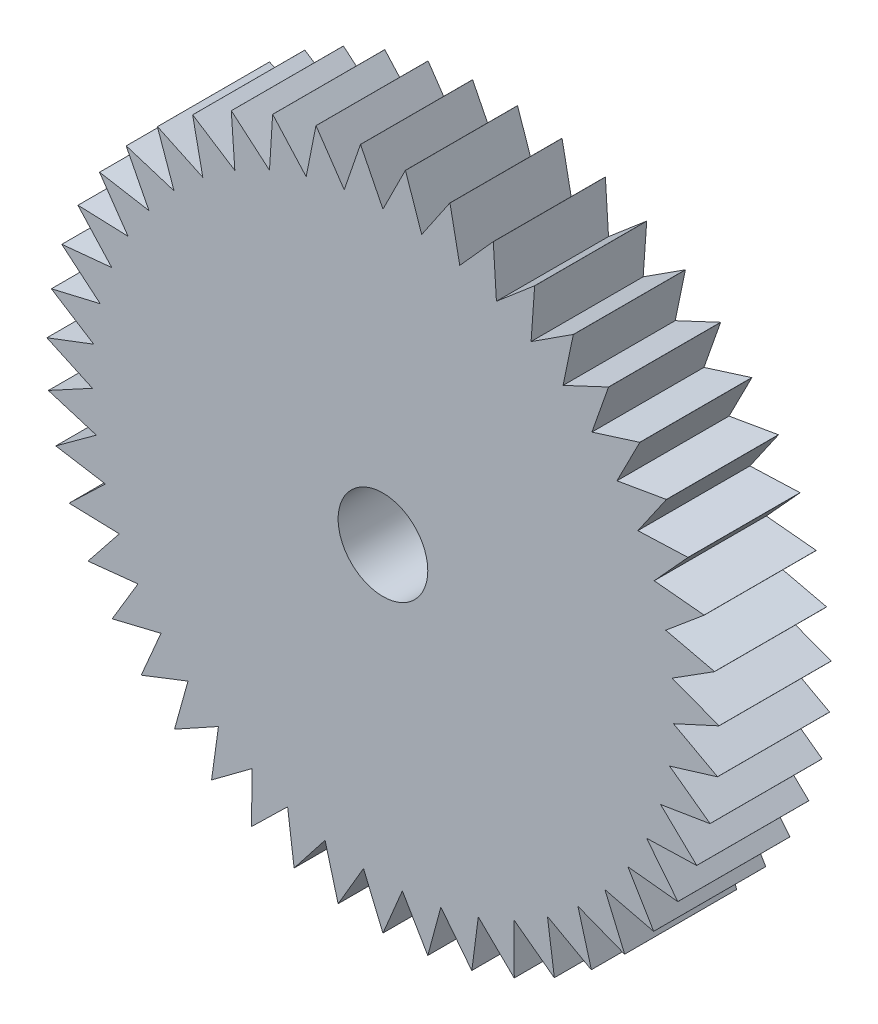
SolidWorks part; units mm, degrees
ref_plane "Alzado" through (0, 0, 0) normal (0, 0, 1) x (1, 0, 0)
ref_plane "Planta" through (0, 0, 0) normal (0, 1, 0) x (1, 0, 0)
ref_plane "Vista lateral" through (0, 0, 0) normal (1, 0, 0) x (0, 0, -1)
sketch "Croquis2" plane through (0, 0, 0) normal (0, 0, 1) x (1, 0, 0)
  circle A0 centre (0, 0) radius 2
  circle A1 centre (0, 0) radius 15
  dimension "D1" = 4
  dimension "D2" = 30
extrude "Saliente-Extruir1" add sketch "Croquis2" along normal blind 5
sketch "Croquis3" plane through (0, 0, 5) normal (0, 0, 1) x (1, 0, 0)
  line L0 (-1, 14.9666) -> (0, 12.9666)
  line L1 (0, 12.9666) -> (1, 14.9666)
  line L2 (-1, 14.9666) -> (1, 14.9666) construction
  line L3 (1.0038, 14.9664) -> (1.7283, 12.8509)
  line L4 (1.7283, 12.8509) -> (2.9859, 14.6998)
  line L5 (2.9896, 14.699) -> (3.4257, 12.5059)
  line L6 (3.4257, 12.5059) -> (4.9186, 14.1707)
  line L7 (4.9222, 14.1694) -> (5.062, 11.9377)
  line L8 (5.062, 11.9377) -> (6.7635, 13.3886)
  line L9 (6.7668, 13.3869) -> (6.608, 11.1565)
  line L10 (6.608, 11.1565) -> (8.4876, 12.3677)
  line L11 (8.4908, 12.3656) -> (8.0361, 10.1762)
  line L12 (8.0361, 10.1762) -> (10.0604, 11.1261)
  line L13 (10.0632, 11.1235) -> (9.3207, 9.0143)
  line L14 (9.3207, 9.0143) -> (11.4536, 9.6859)
  line L15 (11.456, 9.683) -> (10.439, 7.6915)
  line L16 (10.439, 7.6915) -> (12.6424, 8.0728)
  line L17 (12.6444, 8.0696) -> (11.3711, 6.2315)
  line L18 (11.3711, 6.2315) -> (13.6056, 6.3157)
  line L19 (13.6072, 6.3123) -> (12.1002, 4.6603)
  line L20 (12.1002, 4.6603) -> (14.326, 4.4459)
  line L21 (14.3271, 4.4423) -> (12.6134, 3.0059)
  line L22 (12.6134, 3.0059) -> (14.7907, 2.4968)
  line L23 (14.7914, 2.4931) -> (12.9015, 1.2979)
  line L24 (12.9015, 1.2979) -> (14.9916, 0.5031)
  line L25 (14.9917, 0.4993) -> (12.9594, -0.4333)
  line L26 (12.9594, -0.4333) -> (14.9249, -1.4996)
  line L27 (14.9245, -1.5033) -> (12.786, -2.1567)
  line L28 (12.786, -2.1567) -> (14.5918, -3.4755)
  line L29 (14.5909, -3.4791) -> (12.3845, -3.8417)
  line L30 (12.3845, -3.8417) -> (13.9984, -5.3893)
  line L31 (13.997, -5.3929) -> (11.7619, -5.4581)
  line L32 (11.7619, -5.4581) -> (13.1552, -7.2071)
  line L33 (13.1533, -7.2104) -> (10.9295, -6.9771)
  line L34 (10.9295, -6.9771) -> (12.0772, -8.8962)
  line L35 (12.0749, -8.8992) -> (9.902, -8.3716)
  line L36 (9.902, -8.3716) -> (10.7837, -10.4265)
  line L37 (10.781, -10.4292) -> (8.6978, -9.6167)
  line L38 (8.6978, -9.6167) -> (9.2977, -11.7708)
  line L39 (9.2948, -11.7732) -> (7.3384, -10.6902)
  line L40 (7.3384, -10.6902) -> (7.6459, -12.9051)
  line L41 (7.6426, -12.907) -> (5.8481, -11.573)
  line L42 (5.8481, -11.573) -> (5.8576, -13.809)
  line L43 (5.8541, -13.8105) -> (4.2534, -12.2492)
  line L44 (4.2534, -12.2492) -> (3.9648, -14.4665)
  line L45 (3.9611, -14.4675) -> (2.5828, -12.7068)
  line L46 (2.5828, -12.7068) -> (2.0012, -14.8659)
  line L47 (1.9974, -14.8664) -> (0.8661, -12.9377)
  line L48 (0.8661, -12.9377) -> (0.0019, -15)
  line L49 (-0.0019, -15) -> (-0.8661, -12.9377)
  line L50 (-0.8661, -12.9377) -> (-1.9974, -14.8664)
  line L51 (-2.0012, -14.8659) -> (-2.5828, -12.7068)
  line L52 (-2.5828, -12.7068) -> (-3.9611, -14.4675)
  line L53 (-3.9648, -14.4665) -> (-4.2534, -12.2492)
  line L54 (-4.2534, -12.2492) -> (-5.8541, -13.8105)
  line L55 (-5.8576, -13.809) -> (-5.8481, -11.573)
  line L56 (-5.8481, -11.573) -> (-7.6426, -12.907)
  line L57 (-7.6459, -12.9051) -> (-7.3384, -10.6902)
  line L58 (-7.3384, -10.6902) -> (-9.2948, -11.7732)
  line L59 (-9.2977, -11.7708) -> (-8.6978, -9.6167)
  line L60 (-8.6978, -9.6167) -> (-10.781, -10.4292)
  line L61 (-10.7837, -10.4265) -> (-9.902, -8.3716)
  line L62 (-9.902, -8.3716) -> (-12.0749, -8.8992)
  line L63 (-12.0772, -8.8962) -> (-10.9295, -6.9771)
  line L64 (-10.9295, -6.9771) -> (-13.1533, -7.2104)
  line L65 (-13.1552, -7.2071) -> (-11.7619, -5.4581)
  line L66 (-11.7619, -5.4581) -> (-13.997, -5.3929)
  line L67 (-13.9984, -5.3893) -> (-12.3845, -3.8417)
  line L68 (-12.3845, -3.8417) -> (-14.5909, -3.4791)
  line L69 (-14.5918, -3.4755) -> (-12.786, -2.1567)
  line L70 (-12.786, -2.1567) -> (-14.9245, -1.5033)
  line L71 (-14.9249, -1.4996) -> (-12.9594, -0.4333)
  line L72 (-12.9594, -0.4333) -> (-14.9917, 0.4993)
  line L73 (-14.9916, 0.5031) -> (-12.9015, 1.2979)
  line L74 (-12.9015, 1.2979) -> (-14.7914, 2.4931)
  line L75 (-14.7907, 2.4968) -> (-12.6134, 3.0059)
  line L76 (-12.6134, 3.0059) -> (-14.3271, 4.4423)
  line L77 (-14.326, 4.4459) -> (-12.1002, 4.6603)
  line L78 (-12.1002, 4.6603) -> (-13.6072, 6.3123)
  line L79 (-13.6056, 6.3157) -> (-11.3711, 6.2315)
  line L80 (-11.3711, 6.2315) -> (-12.6444, 8.0696)
  line L81 (-12.6424, 8.0728) -> (-10.439, 7.6915)
  line L82 (-10.439, 7.6915) -> (-11.456, 9.683)
  line L83 (-11.4536, 9.6859) -> (-9.3207, 9.0143)
  line L84 (-9.3207, 9.0143) -> (-10.0632, 11.1235)
  line L85 (-10.0604, 11.1261) -> (-8.0361, 10.1762)
  line L86 (-8.0361, 10.1762) -> (-8.4908, 12.3656)
  line L87 (-8.4876, 12.3677) -> (-6.608, 11.1565)
  line L88 (-6.608, 11.1565) -> (-6.7668, 13.3869)
  line L89 (-6.7635, 13.3886) -> (-5.062, 11.9377)
  line L90 (-5.062, 11.9377) -> (-4.9222, 14.1694)
  line L91 (-4.9186, 14.1707) -> (-3.4257, 12.5059)
  line L92 (-3.4257, 12.5059) -> (-2.9896, 14.699)
  line L93 (-2.9859, 14.6998) -> (-1.7283, 12.8509)
  line L94 (-1.7283, 12.8509) -> (-1.0038, 14.9664)
  arc A0 (1, 14.9666) -> (-1, 14.9666) centre (0, 0) ccw
  arc A1 (2.9859, 14.6998) -> (1.0038, 14.9664) centre (0, 0) ccw
  arc A2 (4.9186, 14.1707) -> (2.9896, 14.699) centre (0, 0) ccw
  arc A3 (6.7635, 13.3886) -> (4.9222, 14.1694) centre (0, 0) ccw
  arc A4 (8.4876, 12.3677) -> (6.7668, 13.3869) centre (0, 0) ccw
  arc A5 (10.0604, 11.1261) -> (8.4908, 12.3656) centre (0, 0) ccw
  arc A6 (11.4536, 9.6859) -> (10.0632, 11.1235) centre (0, 0) ccw
  arc A7 (12.6424, 8.0728) -> (11.456, 9.683) centre (0, 0) ccw
  arc A8 (13.6056, 6.3157) -> (12.6444, 8.0696) centre (0, 0) ccw
  arc A9 (14.326, 4.4459) -> (13.6072, 6.3123) centre (0, 0) ccw
  arc A10 (14.7907, 2.4968) -> (14.3271, 4.4423) centre (0, 0) ccw
  arc A11 (14.9916, 0.5031) -> (14.7914, 2.4931) centre (0, 0) ccw
  arc A12 (14.9249, -1.4996) -> (14.9917, 0.4993) centre (0, 0) ccw
  arc A13 (14.5918, -3.4755) -> (14.9245, -1.5033) centre (0, 0) ccw
  arc A14 (13.9984, -5.3893) -> (14.5909, -3.4791) centre (0, 0) ccw
  arc A15 (13.1552, -7.2071) -> (13.997, -5.3929) centre (0, 0) ccw
  arc A16 (12.0772, -8.8962) -> (13.1533, -7.2104) centre (0, 0) ccw
  arc A17 (10.7837, -10.4265) -> (12.0749, -8.8992) centre (0, 0) ccw
  arc A18 (9.2977, -11.7708) -> (10.781, -10.4292) centre (0, 0) ccw
  arc A19 (7.6459, -12.9051) -> (9.2948, -11.7732) centre (0, 0) ccw
  arc A20 (5.8576, -13.809) -> (7.6426, -12.907) centre (0, 0) ccw
  arc A21 (3.9648, -14.4665) -> (5.8541, -13.8105) centre (0, 0) ccw
  arc A22 (2.0012, -14.8659) -> (3.9611, -14.4675) centre (0, 0) ccw
  arc A23 (0.0019, -15) -> (1.9974, -14.8664) centre (0, 0) ccw
  arc A24 (-1.9974, -14.8664) -> (-0.0019, -15) centre (0, 0) ccw
  arc A25 (-3.9611, -14.4675) -> (-2.0012, -14.8659) centre (0, 0) ccw
  arc A26 (-5.8541, -13.8105) -> (-3.9648, -14.4665) centre (0, 0) ccw
  arc A27 (-7.6426, -12.907) -> (-5.8576, -13.809) centre (0, 0) ccw
  arc A28 (-9.2948, -11.7732) -> (-7.6459, -12.9051) centre (0, 0) ccw
  arc A29 (-10.781, -10.4292) -> (-9.2977, -11.7708) centre (0, 0) ccw
  arc A30 (-12.0749, -8.8992) -> (-10.7837, -10.4265) centre (0, 0) ccw
  arc A31 (-13.1533, -7.2104) -> (-12.0772, -8.8962) centre (0, 0) ccw
  arc A32 (-13.997, -5.3929) -> (-13.1552, -7.2071) centre (0, 0) ccw
  arc A33 (-14.5909, -3.4791) -> (-13.9984, -5.3893) centre (0, 0) ccw
  arc A34 (-14.9245, -1.5033) -> (-14.5918, -3.4755) centre (0, 0) ccw
  arc A35 (-14.9917, 0.4993) -> (-14.9249, -1.4996) centre (0, 0) ccw
  arc A36 (-14.7914, 2.4931) -> (-14.9916, 0.5031) centre (0, 0) ccw
  arc A37 (-14.3271, 4.4423) -> (-14.7907, 2.4968) centre (0, 0) ccw
  arc A38 (-13.6072, 6.3123) -> (-14.326, 4.4459) centre (0, 0) ccw
  arc A39 (-12.6444, 8.0696) -> (-13.6056, 6.3157) centre (0, 0) ccw
  arc A40 (-11.456, 9.683) -> (-12.6424, 8.0728) centre (0, 0) ccw
  arc A41 (-10.0632, 11.1235) -> (-11.4536, 9.6859) centre (0, 0) ccw
  arc A42 (-8.4908, 12.3656) -> (-10.0604, 11.1261) centre (0, 0) ccw
  arc A43 (-6.7668, 13.3869) -> (-8.4876, 12.3677) centre (0, 0) ccw
  arc A44 (-4.9222, 14.1694) -> (-6.7635, 13.3886) centre (0, 0) ccw
  arc A45 (-2.9896, 14.699) -> (-4.9186, 14.1707) centre (0, 0) ccw
  arc A46 (-1.0038, 14.9664) -> (-2.9859, 14.6998) centre (0, 0) ccw
  point P6 (0, 14.9666)
  point P147 (0, 0)
  dimension "D1" = 2
  dimension "D3" = 30
  dimension "D2" = 2
  dimension "D4" = 47
extrude "Cortar-Extruir2" cut sketch "Croquis3" against normal blind 5
